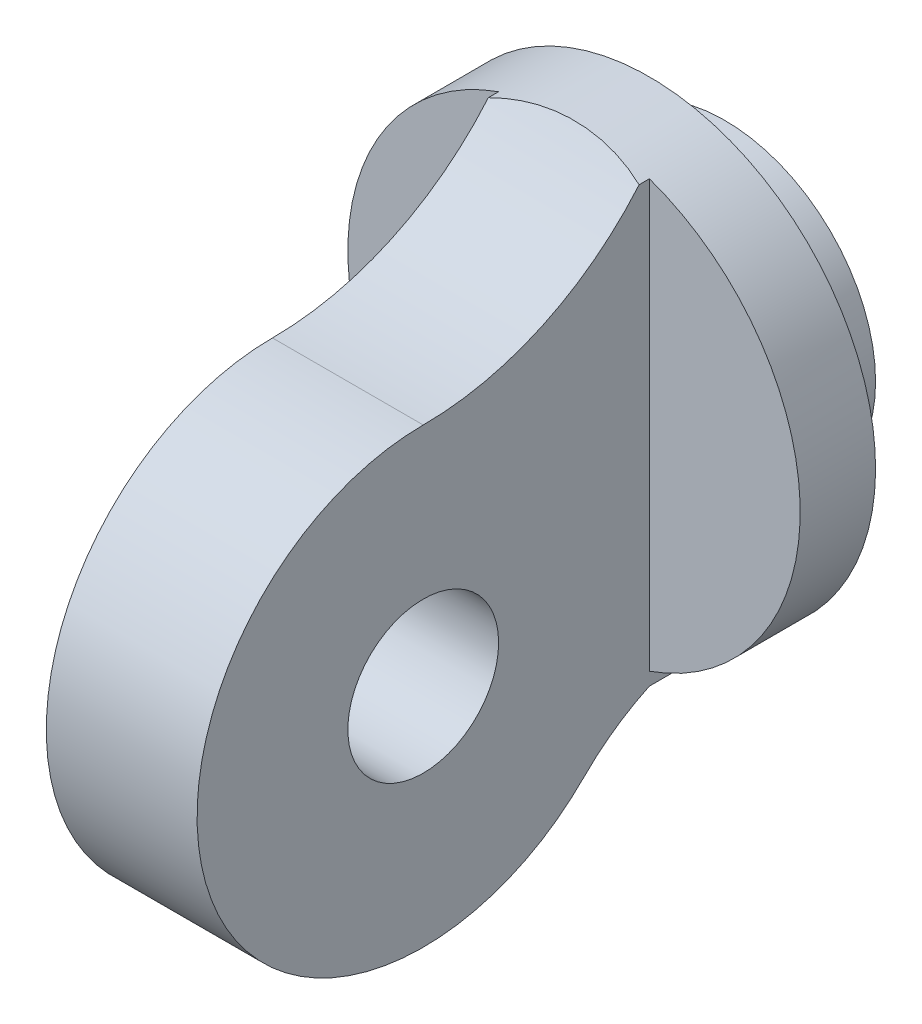
SolidWorks part; units mm, degrees
material "Plain Carbon Steel"
ref_plane "Front Plane" through (0, 0, 0) normal (0, 0, 1) x (1, 0, 0)
ref_plane "Top Plane" through (0, 0, 0) normal (0, 1, 0) x (1, 0, 0)
ref_plane "Right Plane" through (0, 0, 0) normal (1, 0, 0) x (0, 0, -1)
sketch "Sketch1" plane through (0, 0, 0) normal (0, 0, 1) x (1, 0, 0)
  circle A1 centre (0, 0) radius 500
  dimension "D2" = 1000
extrude "Boss-Extrude1" add sketch "Sketch1" along normal blind 250
sketch "Sketch3" plane through (0, 0, 0) normal (0, 0, -1) x (-1, 0, 0)
  circle A0 centre (0, 0) radius 125
  dimension "D1" = 250
extrude "Cut-Extrude1" cut sketch "Sketch3" against normal blind 100
sketch "Sketch4" plane through (0, 0, 250) normal (0, 0, 1) x (1, 0, 0)
  circle A0 centre (0, 0) radius 750
  dimension "D1" = 1500
extrude "Boss-Extrude2" add sketch "Sketch4" along normal blind 250
sketch "Sketch5" plane through (0, 0, 0) normal (1, 0, 0) x (0, 0, -1)
  line L0 (-500, 750) -> (-500, -750) construction
  line L1 (-500, 750) -> (-500, -750)
  line L2 (0, 0) -> (-2325.9915, 0) construction
  arc A0 (-1250, 375) -> (-716.8956, -902.5412) centre (-1250, -375) ccw
  circle A1 centre (-1250, -375) radius 250
  arc A2 (-500, 750) -> (-1250, 375) centre (-1250, 1312.5) cw
  arc A3 (-500, -750) -> (-716.8956, -902.5412) centre (-183.7912, -1430.0823) ccw
  dimension "D2" = 1500
  dimension "D3" = 500
  dimension "D4" = 750
  dimension "D1" = 375
extrude "Boss-Extrude4" add sketch "Sketch5" along normal mid plane 500
sketch "Sketch8" plane through (0, 0, 500) normal (0, 0, -1) x (-1, 0, 0)
  line L2 (-250, 750) -> (-250, 707.1068)
  line L3 (0, 750) -> (-250, 750)
  line L4 (-250, 750) -> (-250, 707.1068)
  line L5 (0, 750) -> (-250, 750)
  arc A1 (0, 750) -> (-250, 707.1068) centre (0, 0) ccw
  arc A2 (0, 750) -> (-250, 707.1068) centre (0, 0) ccw
  dimension "D1" = 0
extrude "Cut-Extrude2" cut sketch "Sketch8" against normal blind 500
sketch "Sketch10" plane through (0, 0, 500) normal (0, 0, -1) x (-1, 0, 0)
  line L2 (250, 750) -> (0, 750)
  line L3 (250, 707.1068) -> (250, 750)
  line L4 (250, 750) -> (0, 750)
  line L5 (250, 707.1068) -> (250, 750)
  arc A1 (250, 707.1068) -> (0, 750) centre (0, 0) ccw
  arc A2 (250, 707.1068) -> (0, 750) centre (0, 0) ccw
  dimension "D1" = 0
extrude "Cut-Extrude5" cut sketch "Sketch10" against normal blind 500
sketch "Sketch11" plane through (0, 0, 500) normal (0, 0, -1) x (-1, 0, 0)
  line L2 (250, -750) -> (250, -707.1068)
  line L3 (0, -750) -> (250, -750)
  line L4 (250, -750) -> (250, -707.1068)
  line L5 (0, -750) -> (250, -750)
  arc A1 (0, -750) -> (250, -707.1068) centre (0, 0) ccw
  arc A2 (0, -750) -> (250, -707.1068) centre (0, 0) ccw
  dimension "D1" = 0
extrude "Boss-Extrude5" add sketch "Sketch11" along normal up to surface (250 mm away) up to face at (750, 0, 250)
sketch "Sketch12" plane through (0, 0, 500) normal (0, 0, -1) x (-1, 0, 0)
  line L2 (-250, -750) -> (0, -750)
  line L3 (-250, -707.1068) -> (-250, -750)
  line L4 (-250, -750) -> (0, -750)
  line L5 (-250, -707.1068) -> (-250, -750)
  arc A1 (-250, -707.1068) -> (0, -750) centre (0, 0) ccw
  arc A2 (-250, -707.1068) -> (0, -750) centre (0, 0) ccw
  dimension "D1" = 0
extrude "Boss-Extrude6" add sketch "Sketch12" along normal up to surface (250 mm away) up to face at (-82.7245, -246.4515, 250)
sketch "Sketch15" plane through (0, 0, 250) normal (0, 0, -1) x (-1, 0, 0)
  line L0 (250, -750) -> (-250, -750) construction
  line L1 (250, -750) -> (-250, -750)
  arc A0 (-250, -750) -> (250, -750) centre (0, 0) ccw
extrude "Boss-Extrude7" add sketch "Sketch15" against normal up to next
